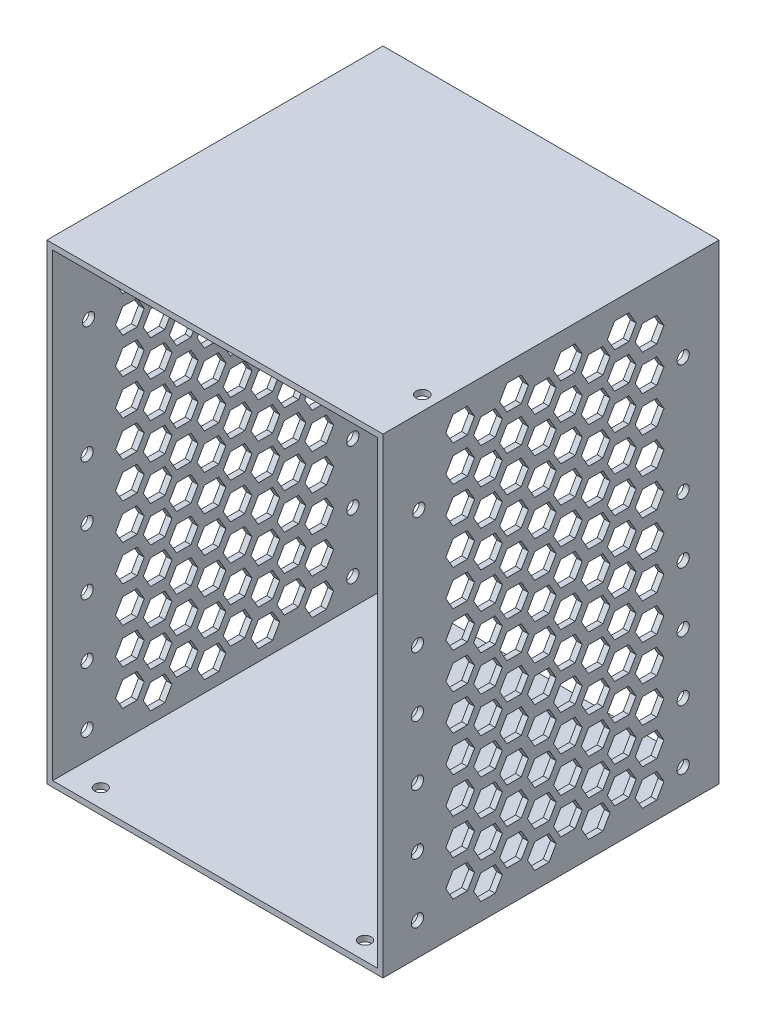
SolidWorks part; units mm, degrees
ref_plane "Front Plane" through (0, 0, 0) normal (0, 0, 1) x (1, 0, 0)
ref_plane "Top Plane" through (0, 0, 0) normal (0, 1, 0) x (1, 0, 0)
ref_plane "Right Plane" through (0, 0, 0) normal (1, 0, 0) x (0, 0, -1)
sketch "Sketch1" plane through (0, 0, 0) normal (0, 0, 1) x (1, 0, 0)
  line L0 (-45.2, 26.84) -> (45.2, 26.84)
  line L1 (45.2, 26.84) -> (45.2, -101.16)
  line L2 (45.2, -101.16) -> (-45.2, -101.16)
  line L3 (-45.2, -101.16) -> (-45.2, 26.84)
  line L5 (-46.8, 28.44) -> (46.8, 28.44)
  line L6 (-46.8, 28.44) -> (-46.8, -102.76)
  line L7 (-46.8, -102.76) -> (46.8, -102.76)
  line L8 (46.8, 28.44) -> (46.8, -102.76)
  dimension "D1" = 90.4
  dimension "D2" = 128
  dimension "D3" = 1.6
  dimension "D4" = 1.6
  dimension "D5" = 1.6
  dimension "D6" = 1.6
  dimension "D7" = 45.2
  dimension "D8" = 45.2
extrude "Boss-Extrude1" add sketch "Sketch1" along normal blind 93.6
sketch "Sketch2" plane through (46.8, 0, 0) normal (1, 0, 0) x (0, 0, -1)
  line L0 (-93.6, 28.44) -> (-93.6, -102.76)
  line L1 (-93.6, 28.44) -> (0, 28.44) construction
  line L2 (-93.6, -102.76) -> (-93.6, 28.44) construction
  line L3 (-93.6, -102.76) -> (0, -102.76) construction
  line L4 (-93.6, -85.36) -> (0, -85.36) construction
  line L5 (0, -102.76) -> (0, 28.44) construction
  line L6 (-93.6, -68.76) -> (0, -68.76) construction
  line L7 (-93.6, -52.16) -> (0, -52.16) construction
  line L8 (-93.6, -35.56) -> (0, -35.56) construction
  line L9 (-93.6, -3.96) -> (0, -3.96) construction
  line L10 (-93.6, -43.86) -> (0, -43.86)
  line L11 (-93.6, -60.46) -> (0, -60.46)
  line L12 (-93.6, -77.06) -> (0, -77.06)
  line L13 (-93.6, -93.66) -> (0, -93.66)
  line L14 (-93.6, -27.26) -> (0, -27.26)
  line L15 (-93.6, 5.14) -> (0, 5.14)
  line L16 (-93.6, -12.26) -> (0, -12.26)
  line L17 (-93.6, -84.56) -> (0, -84.56)
  line L18 (0, -84.56) -> (0, -86.16)
  line L19 (0, -86.16) -> (-93.6, -86.16)
  line L20 (-93.6, -67.96) -> (0, -67.96)
  line L21 (0, -67.96) -> (0, -69.56)
  line L22 (0, -69.56) -> (-93.6, -69.56)
  line L23 (-93.6, -51.36) -> (0, -51.36)
  line L24 (0, -51.36) -> (0, -52.96)
  line L25 (0, -52.96) -> (-93.6, -52.96)
  line L26 (-93.6, -34.76) -> (0, -34.76)
  line L27 (-93.6, -36.36) -> (0, -36.36)
  line L29 (-93.6, -3.16) -> (0, -3.16)
  line L30 (0, -3.16) -> (0, -4.76)
  line L31 (0, -4.76) -> (-93.6, -4.76)
  circle A11 centre (-83.6, 5.14) radius 0.75
  circle A13 centre (-84, -27.26) radius 0.75
  circle A14 centre (-84, -43.86) radius 0.75
  circle A15 centre (-84, -60.46) radius 0.75
  circle A16 centre (-84, -77.06) radius 0.75
  circle A17 centre (-84, -93.66) radius 0.75
  circle A18 centre (-10, 5.14) radius 0.75
  circle A20 centre (-10, -27.26) radius 0.75
  circle A21 centre (-10, -43.86) radius 0.75
  circle A22 centre (-10, -60.46) radius 0.75
  circle A23 centre (-10, -77.06) radius 0.75
  circle A24 centre (-10, -93.66) radius 0.75
  circle A25 centre (-84, -12.26) radius 0.75
  circle A26 centre (-10, -12.26) radius 0.75
  dimension "D7" = 23.3
  dimension "D8" = 23.3
  dimension "D9" = 8.3
  dimension "D10" = 8.3
  dimension "D11" = 8.3
  dimension "D12" = 8.3
  dimension "D13" = 1.5
  dimension "D14" = 10
  dimension "D15" = 10
  dimension "D16" = 1.5
  dimension "D17" = 1.5
  dimension "D18" = 1.5
  dimension "D19" = 1.5
  dimension "D20" = 1.5
  dimension "D21" = 1.5
  dimension "D22" = 1.5
  dimension "D23" = 1.5
  dimension "D24" = 1.5
  dimension "D25" = 1.5
  dimension "D26" = 1.5
  dimension "D1" = 17.4
  dimension "D2" = 16.6
  dimension "D3" = 16.6
  dimension "D4" = 16.6
  dimension "D5" = 31.6
  dimension "D6" = 32.4
  dimension "D27" = 8.3
  dimension "D28" = 0.8
  dimension "D29" = 0.8
  dimension "D30" = 0.8
  dimension "D31" = 0.8
  dimension "D32" = 0.8
  dimension "D33" = 0.8
  dimension "D34" = 0.8
  dimension "D35" = 0.8
  dimension "D36" = 0.8
  dimension "D37" = 0.8
  dimension "D38" = 7.5
extrude "Cut-Extrude1" cut sketch "Sketch2" against normal blind 100 contours L15 A11 | L15 A11 | L15 A18 | L15 A18 | L14 A13 | L14 A13 | L10 A21 | L10 A14 | L11 A15 | L11 A22 | L11 A22 | L12 A16 | L12 A16 | L12 A23 | L13 A17 | L13 A17 | L12 A23 | L13 A24 | L13 A24 | A20
sketch "Sketch6" plane through (46.8, 0, 0) normal (1, 0, 0) x (0, 0, -1)
  line L0 (-76.1, 19.9759) -> (-74.1, 23.44)
  line L1 (-74.1, 23.44) -> (-70.1, 23.44)
  line L2 (-70.1, 23.44) -> (-68.1, 19.9759)
  line L3 (-68.1, 19.9759) -> (-70.1, 16.5118)
  line L4 (-70.1, 16.5118) -> (-74.1, 16.5118)
  line L5 (-74.1, 16.5118) -> (-76.1, 19.9759)
  line L18 (-93.6, 28.44) -> (0, 28.44) construction
  line L19 (-93.6, -102.76) -> (-93.6, 28.44) construction
  line L20 (-68.3557, 15.5047) -> (-66.3557, 18.9688)
  line L21 (-66.3557, 18.9688) -> (-62.3557, 18.9688)
  line L22 (-62.3557, 18.9688) -> (-60.3557, 15.5047)
  line L23 (-60.3557, 15.5047) -> (-62.3557, 12.0406)
  line L24 (-62.3557, 12.0406) -> (-66.3557, 12.0406)
  line L25 (-66.3557, 12.0406) -> (-68.3557, 15.5047)
  dimension "D1" = 120
  dimension "D2" = 120
  dimension "D3" = 120
  dimension "D4" = 4
  dimension "D5" = 4
  dimension "D6" = 4
  dimension "D7" = 4
  dimension "D8" = 5
  dimension "D9" = 17.5
  dimension "D10" = 120
  dimension "D11" = 120
  dimension "D12" = 120
  dimension "D13" = 4
  dimension "D14" = 4
  dimension "D15" = 4
  dimension "D16" = 4
  dimension "D17" = 2.0142
  dimension "D18" = 2.0142
  dimension "D19" = 25.2443
extrude "Cut-Extrude4" cut sketch "Sketch6" against normal blind 100
pattern_linear "LPattern2" count 4 spacing 15 along (0, 0, -1) count 12 spacing 10 along (0, -1, 0) of "Cut-Extrude4"
hole_wizard "M3 Clearance Hole1" positions "Sketch7" profile "Sketch8" hole size "M3" standard "ANSI Metric" end condition through all
sketch "Sketch7" plane through (-46.8, 0, 0) normal (-1, 0, 0) x (0, 0, 1)
  point P0 (10, 5.14)
  point P3 (83.6, 5.14)
  point P6 (10, -27.26)
  point P9 (10, -43.86)
  point P12 (84, -27.26)
  point P15 (84, -43.86)
  point P18 (84, -60.46)
  point P21 (84, -77.06)
  point P26 (10, -93.66)
  point P29 (10, -77.06)
  point P32 (10, -60.46)
  point P40 (84, -93.66)
sketch "Sketch8" plane through (-46.8, 5.14, 10) normal (0, 1, 0) x (0, 0, 1)
  line L0 (0, 0) -> (0, 93.6)
  line L1 (0, 93.6) -> (1.7, 93.6)
  line L2 (1.7, 93.6) -> (1.7, 0)
  line L5 (1.7, 0) -> (0, 0)
  line L11 (0, -6.35) -> (0, 107.95) construction
  dimension "Thru Hole Dia." = 3.4
  dimension "Thru Hole Depth" = 93.6
sketch "Sketch9" plane through (0, 0, 0) normal (0, 0, 1) x (1, 0, 0)
  line L1 (-30, -108.3026) -> (30, -108.3026)
  line L2 (-30, -108.3026) -> (-30, -39.5314)
  line L3 (-30, -39.5314) -> (30, -39.5314)
  line L4 (30, -108.3026) -> (30, -39.5314)
  dimension "D1" = 30
  dimension "D2" = 30
sketch "Sketch10" plane through (0, -102.76, 0) normal (0, -1, 0) x (1, 0, 0)
  line L0 (45.2, 93.6) -> (-45.2, 93.6) construction
  line L3 (-46.8, 0) -> (46.8, 0) construction
  line L5 (-46.8, 0) -> (46.8, 0) construction
  line L6 (-46.8, 93.6) -> (46.8, 93.6) construction
  line L7 (-46.8, 93.6) -> (-46.8, 0) construction
  line L8 (46.8, 93.6) -> (46.8, 0) construction
  circle A0 centre (-36.8, 88.6) radius 2.9453
  circle A1 centre (-36.8, 5) radius 1.9301
  circle A2 centre (36.8, 5) radius 1.9498
  circle A3 centre (36.8, 88.6) radius 2.427
  dimension "D1" = 5
  dimension "D2" = 10
  dimension "D3" = 10
  dimension "D4" = 5
  dimension "D5" = 10
  dimension "D6" = 5
  dimension "D7" = 5
  dimension "D8" = 10
hole_wizard "M3 Clearance Hole2" positions "Sketch11" profile "Sketch12" hole size "M3" standard "ANSI Metric"
sketch "Sketch11" plane through (0, -102.76, 0) normal (0, -1, 0) x (-1, 0, 0)
  point P0 (-36.8, -5)
  point P3 (-36.8, -88.6)
  point P6 (36.8, -88.6)
  point P9 (36.8, -5)
sketch "Sketch12" plane through (36.8, -102.76, 5) normal (1, 0, 0) x (0, 0, -1)
  line L0 (0, 0) -> (0, 1.6)
  line L1 (0, 1.6) -> (1.7, 1.6)
  line L2 (1.7, 1.6) -> (1.7, 0)
  line L5 (1.7, 0) -> (0, 0)
  line L11 (0, -6.35) -> (0, 107.95) construction
  dimension "Thru Hole Dia." = 3.4
  dimension "Thru Hole Depth" = 1.6
sketch "Sketch16" plane through (0, 28.44, 0) normal (0, 1, 0) x (1, 0, 0)
  line L0 (46.8, -93.6) -> (46.8, 0) construction
  line L1 (46.8, -93.6) -> (-46.8, -93.6) construction
  circle A0 centre (42.75, -78.6) radius 1.75
  dimension "D1" = 3.5
  dimension "D2" = 4.05
  dimension "D3" = 15
extrude "Cut-Extrude6" cut sketch "Sketch16" against normal blind 141
